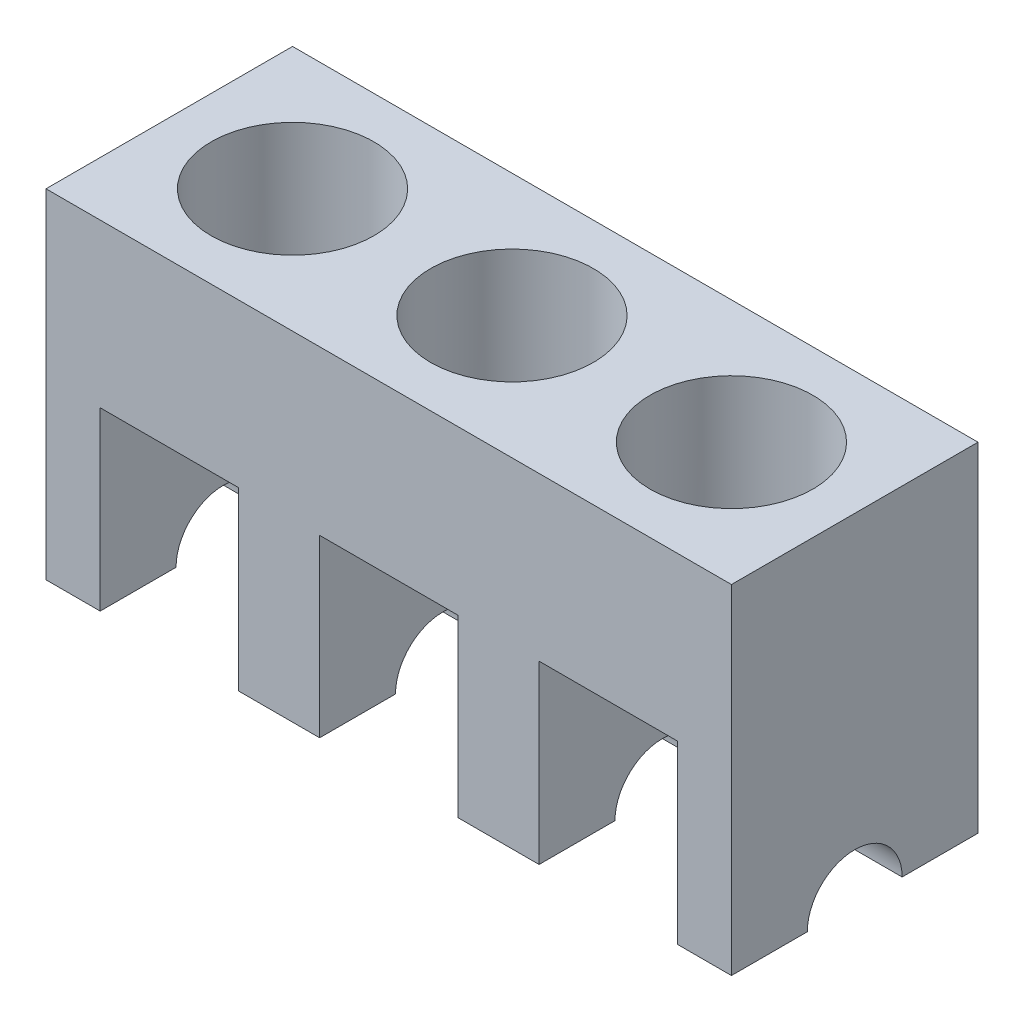
SolidWorks part; units mm, degrees
ref_plane "Front Plane" through (0, 0, 0) normal (0, 0, 1) x (1, 0, 0)
ref_plane "Top Plane" through (0, 0, 0) normal (0, 1, 0) x (1, 0, 0)
ref_plane "Right Plane" through (0, 0, 0) normal (1, 0, 0) x (0, 0, -1)
sketch "Sketch1" plane through (0, 0, 0) normal (0, 1, 0) x (1, 0, 0)
  line L0 (-56.7788, 2284.415) -> (-56.7788, -26.985)
  line L1 (-56.7788, -26.985) -> (6369.4212, -26.985)
  line L2 (6369.4212, -26.985) -> (6369.4212, 2284.415)
  line L3 (6369.4212, 2284.415) -> (-56.7788, 2284.415)
  dimension "D1" = 6426.2
  dimension "D2" = 2311.4
extrude "Boss-Extrude1" add sketch "Sketch1" along normal blind 3175
sketch "Sketch2" plane through (0, 3175, 0) normal (0, 1, 0) x (1, 0, 0)
  line L0 (-56.7788, 2284.415) -> (-56.7788, -26.985) construction
  line L1 (6369.4212, 2284.415) -> (-56.7788, 2284.415) construction
  line L3 (1098.9212, 1128.715) -> (8216.5621, 1128.715) construction
  line L4 (-56.7788, -26.985) -> (6369.4212, -26.985) construction
  circle A0 centre (1098.9212, 1128.715) radius 763.27
  circle A1 centre (3156.3212, 1128.715) radius 763.27
  circle A2 centre (5213.7212, 1128.715) radius 763.27
  point P2 (0, 0)
  point P14 (0, 0)
  point P15 (0, 0)
  dimension "D1" = 1155.7
  dimension "D3" = 1526.54
  dimension "D2" = 1155.7
  dimension "D4" = 1155.7
  dimension "D5" = 2057.4
  dimension "D6" = 1155.7
  dimension "D7" = 2057.4
extrude "Cut-Extrude1" cut sketch "Sketch2" against normal offset from surface (2057.4 mm away) 2057.4 up to face at (3156.3212, 3175, -1128.715)
sketch "Sketch6" plane through (0, 0, 0) normal (0, 0, 1) x (1, 0, 0)
  line L5 (2508.6212, -7.1583) -> (3804.0212, -7.1583)
  line L6 (2508.6212, -7.1583) -> (2508.6212, 1643.8417)
  line L7 (2508.6212, 1643.8417) -> (3804.0212, 1643.8417)
  line L8 (3804.0212, -7.1583) -> (3804.0212, 1643.8417)
  line L9 (4566.0212, 0) -> (5861.4212, 0)
  line L10 (4566.0212, 0) -> (4566.0212, 1651)
  line L11 (4566.0212, 1651) -> (5861.4212, 1651)
  line L12 (5861.4212, 0) -> (5861.4212, 1651)
  line L13 (6369.4212, 3175) -> (6369.4212, 0) construction
  line L18 (451.2212, 0) -> (1746.6212, 0)
  line L19 (451.2212, 0) -> (451.2212, 1651)
  line L20 (451.2212, 1651) -> (1746.6212, 1651)
  line L21 (1746.6212, 0) -> (1746.6212, 1651)
  line L22 (-56.7788, 3175) -> (-56.7788, 0) construction
  line L23 (-56.7788, 0) -> (6369.4212, 0) construction
  dimension "D1" = 508
  dimension "D2" = 1651
  dimension "D3" = 0
  dimension "D4" = 762
  dimension "D5" = 508
  dimension "D6" = 0
  dimension "D7" = 1651
extrude "Cut-Extrude3" cut sketch "Sketch6" against normal through all both and the other way through all
sketch "Sketch7" plane through (6369.4212, 0, 0) normal (1, 0, 0) x (0, 0, -1)
  line L0 (1128.715, 3175) -> (1128.715, -635.9583) construction
  line L1 (-26.985, 3175) -> (2284.415, 3175) construction
  line L2 (-26.985, 0) -> (2284.415, 0) construction
  circle A0 centre (1128.715, 0) radius 444.5
extrude "Cut-Extrude4" cut sketch "Sketch7" against normal through all both and the other way through all
